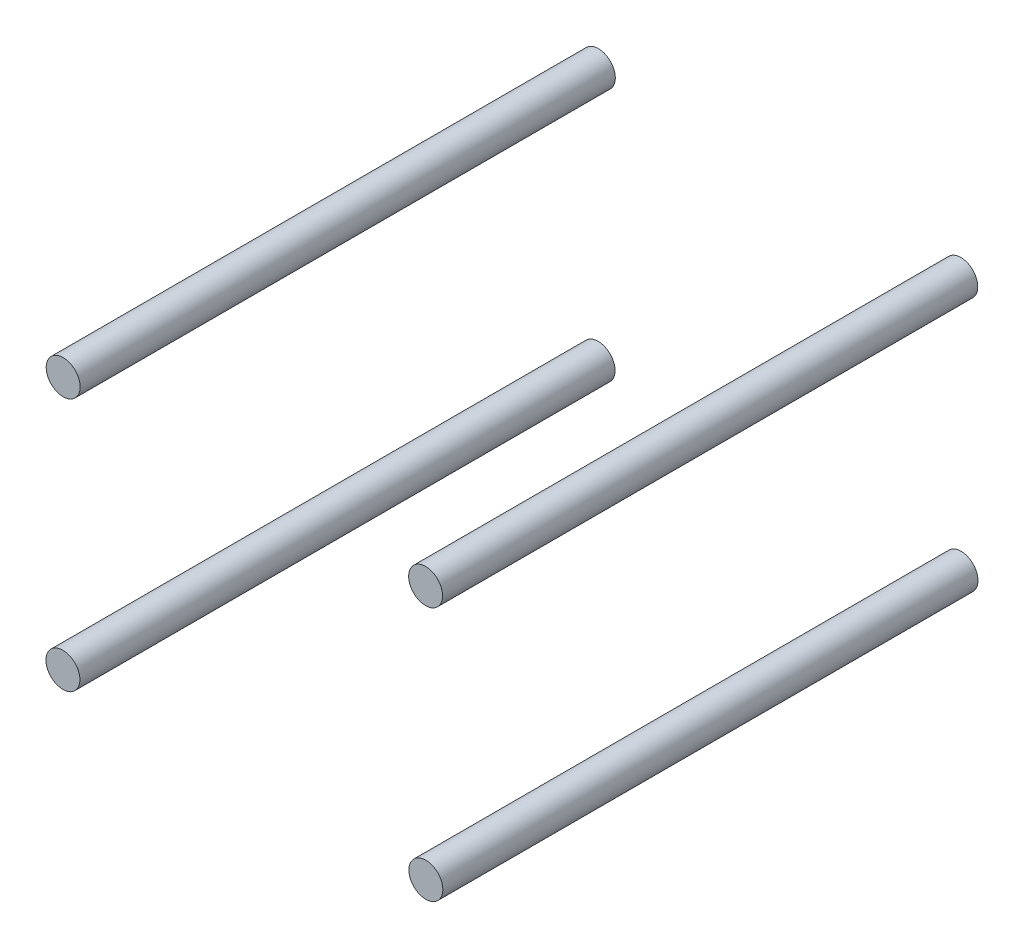
SolidWorks part; units mm, degrees
ref_plane "Front Plane" through (0, 0, 0) normal (0, 0, 1) x (1, 0, 0)
ref_plane "Top Plane" through (0, 0, 0) normal (0, 1, 0) x (1, 0, 0)
ref_plane "Right Plane" through (0, 0, 0) normal (1, 0, 0) x (0, 0, -1)
sketch "Sketch1" plane through (0, 0, 0) normal (0, 0, 1) x (1, 0, 0)
  circle A0 centre (6450.3756, 3611.5807) radius 2.921
  circle A1 centre (6512.8358, 3611.5224) radius 2.921
  circle A2 centre (6512.7942, 3655.2882) radius 2.921
  circle A3 centre (6450.4164, 3655.2289) radius 2.921
extrude "Boss-Extrude1" add sketch "Sketch1" along normal blind 92.1106
